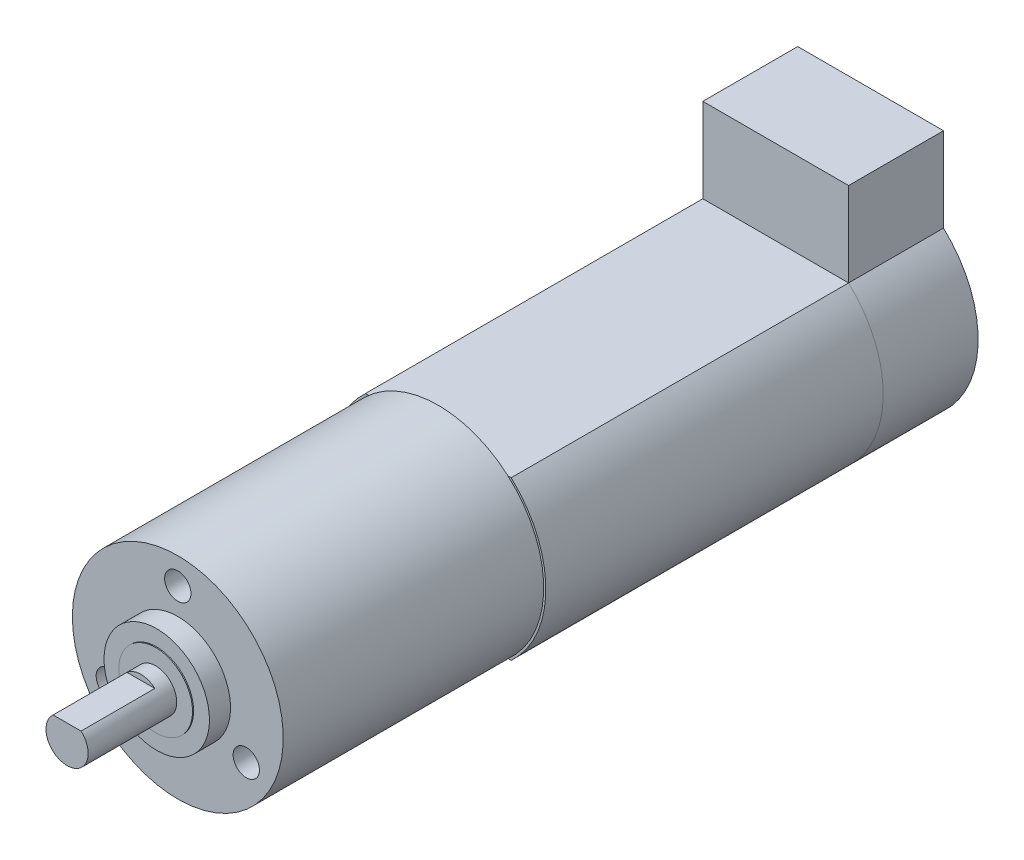
SolidWorks part; units mm, degrees
ref_plane "Front Plane" through (0, 0, 0) normal (0, 0, 1) x (1, 0, 0)
ref_plane "Top Plane" through (0, 0, 0) normal (0, 1, 0) x (1, 0, 0)
ref_plane "Right Plane" through (0, 0, 0) normal (1, 0, 0) x (0, 0, -1)
sketch "Sketch1" plane through (0, 0, 0) normal (0, 0, 1) x (1, 0, 0)
  line L0 (-1.3229, 1.5) -> (1.3229, 1.5)
  arc A0 (-1.3229, 1.5) -> (1.3229, 1.5) centre (0, 0) ccw
  dimension "D1" = 2
  dimension "D2" = 1.5
extrude "Boss-Extrude1" add sketch "Sketch1" against normal blind 7
sketch "Sketch2" plane through (0, 0, -7) normal (0, 0, -1) x (-1, 0, 0)
  circle A0 centre (0, 0) radius 2
extrude "Boss-Extrude2" add sketch "Sketch2" along normal blind 1.4
sketch "Sketch3" plane through (0, 0, -8.4) normal (0, 0, -1) x (-1, 0, 0)
  circle A0 centre (0, 0) radius 3.5
  dimension "D1" = 7
extrude "Boss-Extrude3" add sketch "Sketch3" along normal blind 0.1
sketch "Sketch4" plane through (0, 0, -8.5) normal (0, 0, -1) x (-1, 0, 0)
  circle A0 centre (0, 0) radius 5
  dimension "D1" = 10
extrude "Boss-Extrude4" add sketch "Sketch4" along normal blind 2 separate body
sketch "Sketch5" plane through (0, 0, -10.5) normal (0, 0, -1) x (-1, 0, 0)
  circle A0 centre (0, 0) radius 10
  dimension "D1" = 20
extrude "Boss-Extrude5" add sketch "Sketch5" along normal blind 24.7
sketch "Sketch6" plane through (0, 0, -10.5) normal (0, 0, 1) x (1, 0, 0)
  line L0 (0, 0) -> (0, 7.5) construction
  line L1 (6.4952, -3.75) -> (0, 0) construction
  line L2 (0, 0) -> (-6.4952, -3.75) construction
  line L3 (0, 0) -> (0, 10) construction
  circle A0 centre (0, 0) radius 7.5 construction
  circle A1 centre (0, 7.5) radius 1.25
  circle A2 centre (6.4952, -3.75) radius 1.25
  circle A3 centre (-6.4952, -3.75) radius 1.25
  circle A4 centre (0, 0) radius 10 construction
  dimension "D1" = 15
  dimension "D5" = 2.5
  dimension "D2" = 120
  dimension "D3" = 120
  dimension "D4" = 0
extrude "Screw Holes" cut sketch "Sketch6" against normal blind 5
sketch "Sketch10" plane through (0, 0, -35.2) normal (0, 0, -1) x (-1, 0, 0)
  line L0 (-6.913, 7.5) -> (6.913, 7.5)
  line L1 (-6.913, -7.5) -> (6.913, -7.5)
  arc A0 (-6.913, 7.5) -> (-6.913, -7.5) centre (0, 0) ccw
  arc A1 (6.913, -7.5) -> (6.913, 7.5) centre (0, 0) ccw
  dimension "D1" = 10.2
  dimension "D2" = 15
extrude "Motor" add sketch "Sketch10" along normal blind 32 separate body
sketch "Sketch11" plane through (0, 0, -67.2) normal (0, 0, -1) x (-1, 0, 0)
  line L1 (-6.913, -7.5) -> (6.913, -7.5)
  line L4 (-6.913, 7.5) -> (-6.913, 15.5)
  line L5 (-6.913, 15.5) -> (6.913, 15.5)
  line L6 (6.913, 7.5) -> (6.913, 15.5)
  arc A0 (6.913, -7.5) -> (6.913, 7.5) centre (0, 0) ccw
  arc A1 (-6.913, 7.5) -> (-6.913, -7.5) centre (0, 0) ccw
  dimension "D1" = 23
extrude "Encoder" add sketch "Sketch11" along normal blind 9 separate body
